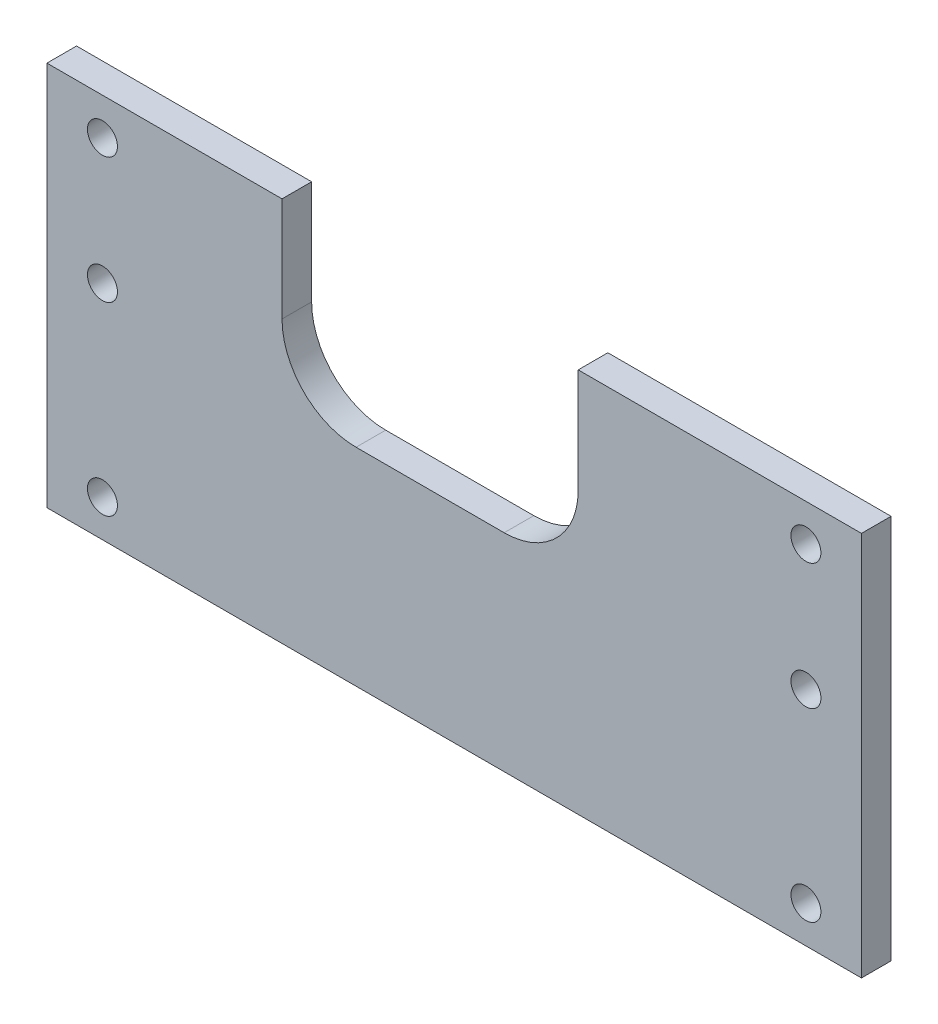
SolidWorks part; units mm, degrees
ref_plane "前视基准面" through (0, 0, 0) normal (0, 0, 1) x (1, 0, 0)
ref_plane "上视基准面" through (0, 0, 0) normal (0, 1, 0) x (1, 0, 0)
ref_plane "右视基准面" through (0, 0, 0) normal (1, 0, 0) x (0, 0, -1)
other "Configuration Table"
sketch "草图1" plane through (0, 0, 0) normal (0, 0, 1) x (1, 0, 0)
  line L1 (-55, -26) -> (55, -26)
  line L2 (-55, -26) -> (-55, 26)
  line L3 (-55, 26) -> (55, 26)
  line L4 (55, -26) -> (55, 26)
  line L5 (-55, -26) -> (55, 26) construction
  line L6 (-55, 26) -> (55, -26) construction
  point P0 (0, 0)
  dimension "D1" = 110
  dimension "D2" = 52
extrude "凸台-拉伸1" add sketch "草图1" along normal blind 4
sketch "草图2" plane through (0, 0, 0) normal (0, 0, -1) x (-1, 0, 0)
  line L0 (0, 0) -> (0, 31.9812) construction
  circle A0 centre (-47.5, -21) radius 1.65 construction
  circle A1 centre (-47.5, 4) radius 1.65 construction
  circle A2 centre (-47.5, 21) radius 1.75 construction
  circle A3 centre (-47.5, -21) radius 1.65 construction
  circle A4 centre (-47.5, 4) radius 1.65 construction
  circle A5 centre (-47.5, 21) radius 1.75 construction
  circle A6 centre (-47.5, 21) radius 2.025
  circle A7 centre (-47.5, 4) radius 2.025
  circle A8 centre (-47.5, -21) radius 2.025
  circle A9 centre (47.5, 21) radius 1.75 construction
  circle A10 centre (47.5, 4) radius 1.65 construction
  circle A11 centre (47.5, -21) radius 1.65 construction
  circle A12 centre (47.5, -21) radius 2.025
  circle A13 centre (47.5, 4) radius 2.025
  circle A14 centre (47.5, 21) radius 2.025
  dimension "D1" = 4.05
extrude "切除-拉伸1" cut sketch "草图2" against normal blind 4
sketch "草图3" plane through (0, 0, 0) normal (0, 0, -1) x (-1, 0, 0)
  line L0 (3.25, 28.45) -> (3.25, 14.45) construction
  line L2 (-16.75, 1.95) -> (23.25, 1.95)
  line L3 (-16.75, 1.95) -> (-16.75, 40.95)
  line L4 (-16.75, 40.95) -> (23.25, 40.95)
  line L5 (23.25, 1.95) -> (23.25, 40.95)
  line L6 (-15.75, 14.45) -> (34.25, 14.45)
  line L7 (34.25, 14.45) -> (34.25, 19.45)
  line L8 (34.25, 19.45) -> (22.25, 19.45)
  line L9 (22.25, 19.45) -> (22.25, 26.45)
  line L10 (20.25, 28.45) -> (-13.75, 28.45)
  line L11 (-15.75, 26.45) -> (-15.75, 14.45)
  line L12 (-15.75, 14.45) -> (34.25, 14.45) construction
  line L13 (34.25, 14.45) -> (34.25, 19.45) construction
  line L14 (34.25, 19.45) -> (22.25, 19.45) construction
  line L15 (22.25, 19.45) -> (22.25, 26.45) construction
  line L16 (20.25, 28.45) -> (-13.75, 28.45) construction
  line L17 (-15.75, 26.45) -> (-15.75, 14.45) construction
  line L18 (-16.75, 1.95) -> (23.25, 40.95) construction
  line L19 (-16.75, 40.95) -> (23.25, 1.95) construction
  arc A2 (22.25, 26.45) -> (20.25, 28.45) centre (20.25, 26.45) ccw
  arc A3 (-13.75, 28.45) -> (-15.75, 26.45) centre (-13.75, 26.45) ccw
  arc A4 (22.25, 26.45) -> (20.25, 28.45) centre (20.25, 26.45) ccw construction
  arc A5 (-13.75, 28.45) -> (-15.75, 26.45) centre (-13.75, 26.45) ccw construction
  point P9 (3.25, 21.45)
  dimension "D2" = 1
  dimension "D3" = 25
  dimension "D1" = 0
extrude "切除-拉伸2" cut sketch "草图3" against normal blind 4
fillet "圆角1" radius 10 2 edges at (-23.25, 1.95, 2) (16.75, 1.95, 2)
sketch "草图4" plane through (0, 0, 0) normal (0, 0, -1) x (-1, 0, 0)
  circle A0 centre (31.75, -5.05) radius 1.25 construction
  circle A1 centre (31.75, 16.95) radius 1.25 construction
  circle A2 centre (31.75, -5.05) radius 1.25
  circle A3 centre (31.75, 16.95) radius 1.25
  circle A4 centre (-43.25, -5.05) radius 1.25 construction
  circle A5 centre (-43.25, 16.95) radius 1.25 construction
  circle A6 centre (-43.25, -5.05) radius 1.25
  circle A7 centre (-43.25, 16.95) radius 1.25
